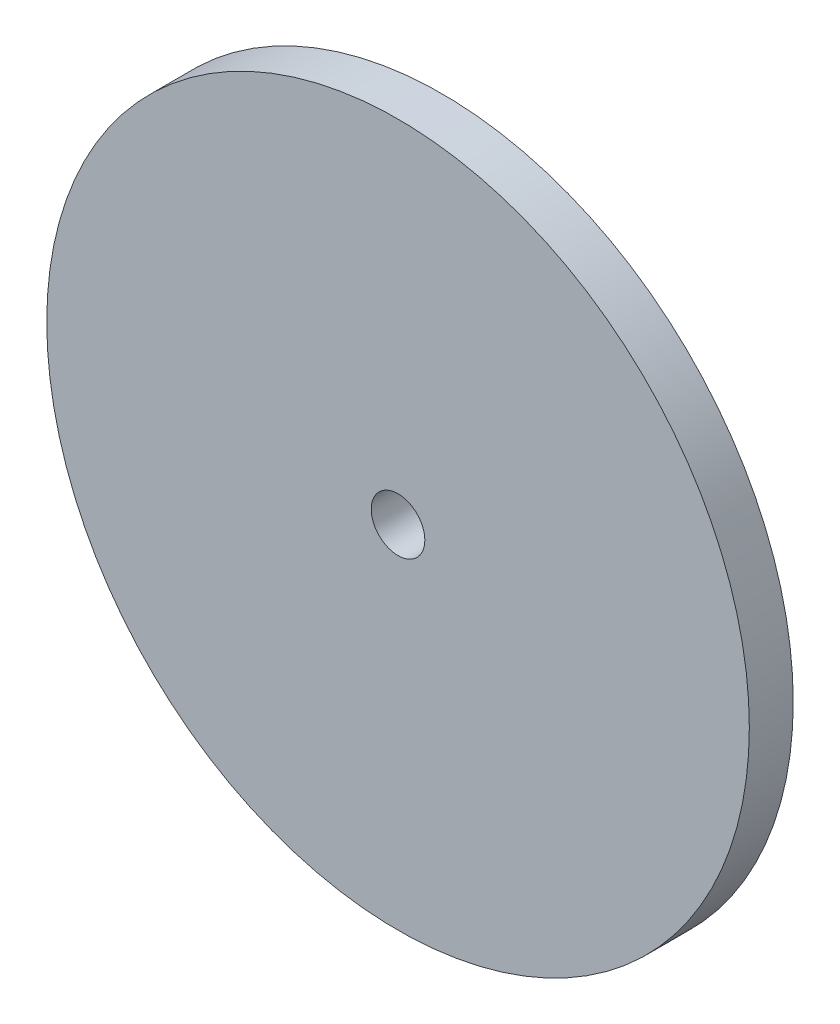
SolidWorks part; units mm, degrees
material "Balsa"
ref_plane "Front Plane" through (0, 0, 0) normal (0, 0, 1) x (1, 0, 0)
ref_plane "Top Plane" through (0, 0, 0) normal (0, 1, 0) x (1, 0, 0)
ref_plane "Right Plane" through (0, 0, 0) normal (1, 0, 0) x (0, 0, -1)
sketch "Sketch1" plane through (0, 0, 0) normal (0, 0, 1) x (1, 0, 0)
  circle A1 centre (0, 0) radius 40
  circle A2 centre (0, 0) radius 3.05
  dimension "D1" = 80
  dimension "D2" = 6.1
extrude "Boss-Extrude1" add sketch "Sketch1" along normal blind 5
